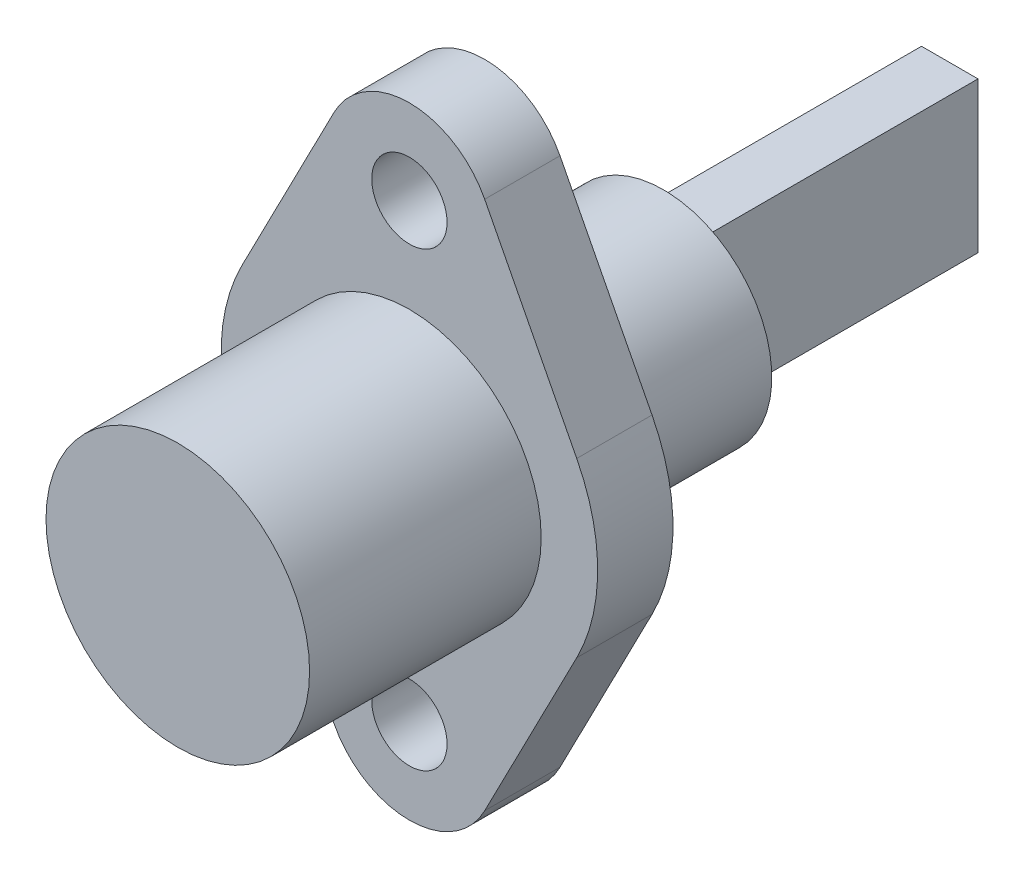
SolidWorks part; units mm, degrees
material "Custom Plastic"
ref_plane "X-Y Datum" through (0, 0, 0) normal (0, 0, 1) x (1, 0, 0)
ref_plane "X-Z Datum" through (0, 0, 0) normal (0, 1, 0) x (1, 0, 0)
ref_plane "Y-Z Datum" through (0, 0, 0) normal (1, 0, 0) x (0, 0, -1)
sketch "Sketch1" plane through (0, 0, 0) normal (0, 0, 1) x (1, 0, 0)
  line L0 (0, 17) -> (0, -17) construction
  line L1 (-10, 0) -> (10, 0) construction
  line L2 (-3.7696, 14.5084) -> (-8.8878, 4.5833)
  line L3 (3.7696, 14.5084) -> (8.8878, 4.5833)
  line L4 (3.7696, -14.5084) -> (8.8878, -4.5833)
  line L5 (-3.7696, -14.5084) -> (-8.8878, -4.5833)
  line L6 (0, 12) -> (0, -12) construction
  circle A0 centre (0, 0) radius 10
  circle A5 centre (0, 12) radius 2
  circle A6 centre (0, -12) radius 2
  circle A7 centre (0, 12) radius 4.5
  circle A8 centre (0, -12) radius 4.5
  point P4 (0, 0)
  point P8 (0, 0)
  point P26 (0, 0)
  dimension "D3" = 4
  dimension "D5" = 24
  dimension "D1" = 34
  dimension "D2" = 20
  dimension "D4" = 24
  dimension "D6" = 2.5
extrude "Boss-Extrude1" add sketch "Sketch1" along normal blind 4 contours A7 A0 A5 | A7 L2 A0 | A7 A0 L3 | A0 A8 A7 | A0 A7 | L5 A8 A0 | A8 A0 | A8 A0 A6 | A0 A8 L4
sketch "Sketch2" plane through (0, 0, 4) normal (0, 0, 1) x (1, 0, 0)
  circle A0 centre (0, 0) radius 7
  dimension "D1" = 14
extrude "Boss-Extrude2" add sketch "Sketch2" along normal blind 12.3
sketch "Sketch3" plane through (0, 0, 0) normal (0, 0, -1) x (-1, 0, 0)
  circle A0 centre (0, 0) radius 7.5
  dimension "D1" = 15
extrude "Boss-Extrude3" add sketch "Sketch3" along normal blind 0.5
sketch "Sketch4" plane through (0, 0, -0.5) normal (0, 0, -1) x (-1, 0, 0)
  line L1 (-1.5, 4) -> (1.5, 4)
  line L2 (-1.5, 4) -> (-1.5, -4)
  line L3 (-1.5, -4) -> (1.5, -4)
  line L4 (1.5, 4) -> (1.5, -4)
  line L5 (-1.5, 4) -> (1.5, -4) construction
  line L6 (-1.5, -4) -> (1.5, 4) construction
  point P0 (0, 0)
  dimension "D1" = 8
  dimension "D2" = 3
extrude "Boss-Extrude4" add sketch "Sketch4" along normal blind 24.2
sketch "Sketch5" plane through (0, 0, -0.5) normal (0, 0, -1) x (-1, 0, 0)
  circle A0 centre (0, 0) radius 5.75
  dimension "D1" = 11.5
extrude "Boss-Extrude5" add sketch "Sketch5" along normal blind 9
